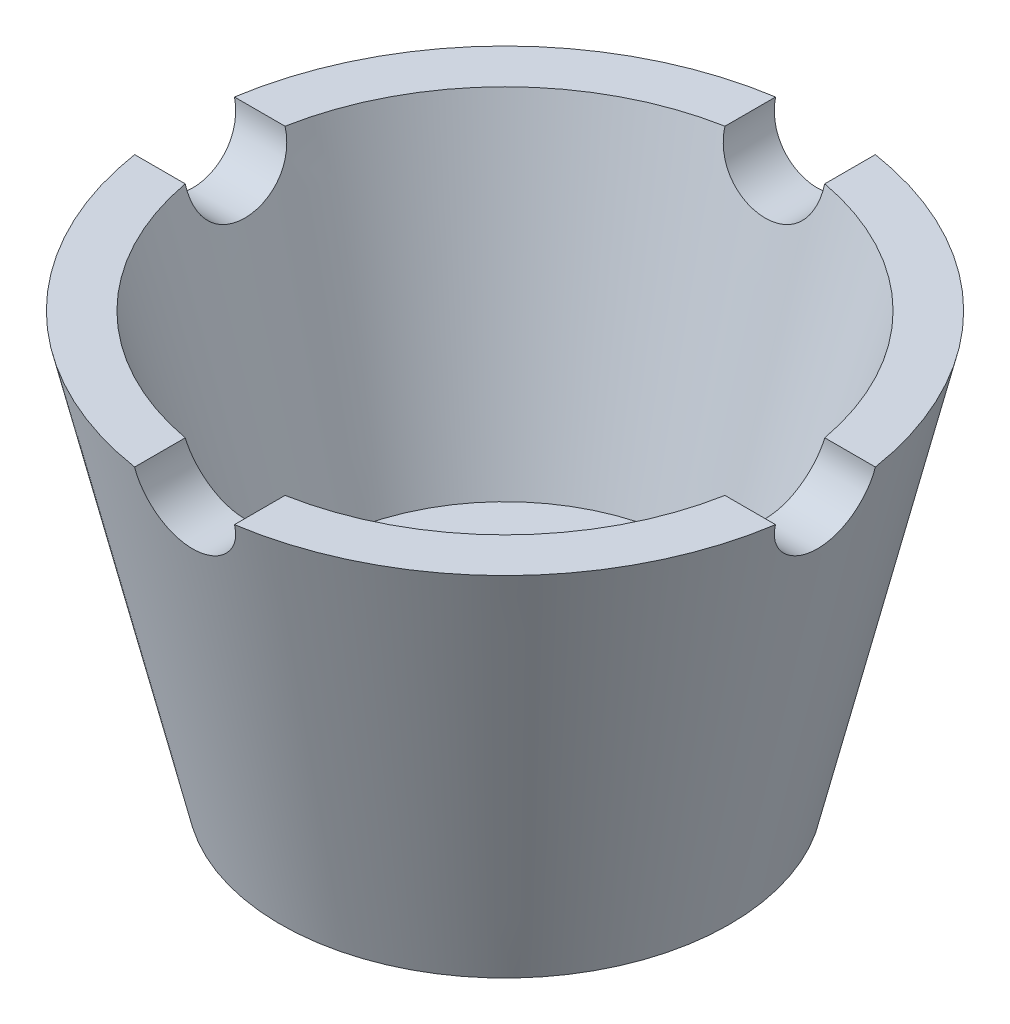
SolidWorks part; units mm, degrees
material "Gray Cast Iron (SN)"
ref_plane "Front Plane" through (0, 0, 0) normal (0, 0, 1) x (1, 0, 0)
ref_plane "Top Plane" through (0, 0, 0) normal (0, 1, 0) x (1, 0, 0)
ref_plane "Right Plane" through (0, 0, 0) normal (1, 0, 0) x (0, 0, -1)
sketch "Sketch4" plane through (0, 0, 0) normal (0, 0, 1) x (1, 0, 0)
  line L0 (11.25, 0) -> (11.25, 12)
  line L1 (11.25, 12) -> (19, 12)
  line L2 (11.25, 0) -> (22.5, 0)
  line L3 (0, 0) -> (0, 52.6957) construction
  line L4 (22.5, 0) -> (32.5, 42)
  line L5 (19, 12) -> (27.5, 42)
  line L6 (27.5, 42) -> (32.5, 42)
  dimension "D1" = 12
  dimension "D2" = 22.5
  dimension "D3" = 45
  dimension "D4" = 38
  dimension "D5" = 42
  dimension "D6" = 65
  dimension "D7" = 5
revolve "Revolve1" add sketch "Sketch4" angle 360 about L3
sketch "Sketch5" plane through (0, 0, 0) normal (0, 0, 1) x (1, 0, 0)
  line L0 (32.5, 42) -> (-32.5, 42) construction
  circle A0 centre (0, 42) radius 5
  dimension "D1" = 10
extrude "Cut-Extrude1" cut sketch "Sketch5" against normal up to next
pattern_circular "CirPattern1" count 4 over 360 about axis through (0, 42, 0) along (0, -1, 0) of "Cut-Extrude1"
